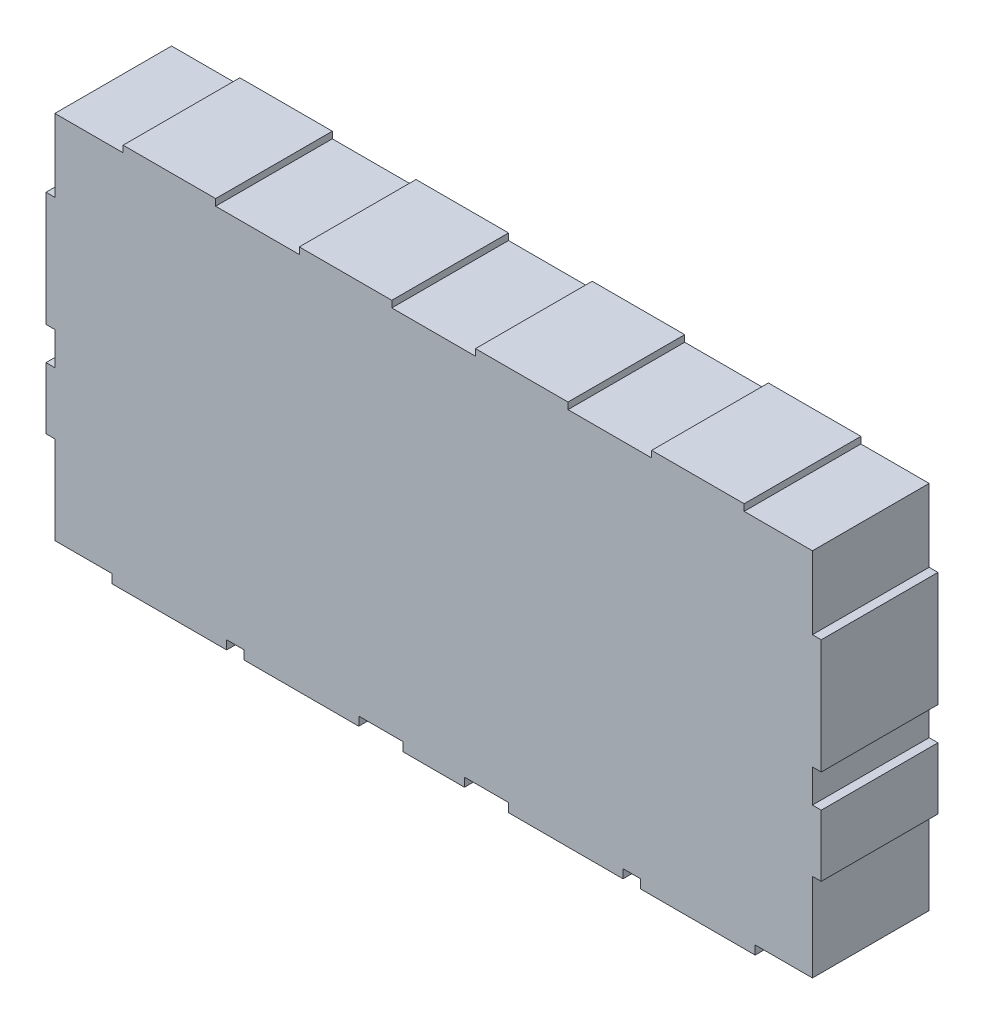
SolidWorks part; units mm, degrees
ref_plane "前视基准面" through (0, 0, 0) normal (0, 0, 1) x (1, 0, 0)
ref_plane "上视基准面" through (0, 0, 0) normal (0, 1, 0) x (1, 0, 0)
ref_plane "右视基准面" through (0, 0, 0) normal (1, 0, 0) x (0, 0, -1)
sketch "草图1" plane through (0, 0, 0) normal (0, 0, 1) x (1, 0, 0)
  line L0 (7.05, 4.35) -> (7.05, 4.2)
  line L1 (7.05, 4.2) -> (8.6, 4.2)
  line L2 (8.6, 4.2) -> (8.6, 2.55)
  line L3 (8.6, 2.55) -> (8.8, 2.55)
  line L4 (8.8, 2.55) -> (8.8, -0.05)
  line L5 (8.8, -0.05) -> (8.6, -0.05)
  line L6 (8.6, -0.05) -> (8.6, -0.8)
  line L7 (8.6, -0.8) -> (8.8, -0.8)
  line L8 (8.8, -0.8) -> (8.8, -2.2)
  line L9 (8.8, -2.2) -> (8.6, -2.2)
  line L10 (8.6, -2.2) -> (8.6, -4.2)
  line L11 (8.6, -4.2) -> (7.3, -4.2)
  line L12 (7.3, -4.2) -> (7.3, -4.4)
  line L13 (7.3, -4.4) -> (4.7, -4.4)
  line L14 (4.7, -4.4) -> (4.7, -4.2)
  line L15 (4.7, -4.2) -> (4.3, -4.2)
  line L16 (4.3, -4.2) -> (4.3, -4.4)
  line L17 (4.3, -4.4) -> (1.7, -4.4)
  line L18 (1.7, -4.4) -> (1.7, -4.2)
  line L19 (1.7, -4.2) -> (0.7, -4.2)
  line L20 (0.7, -4.2) -> (0.7, -4.4)
  line L21 (0.7, -4.4) -> (-0.7, -4.4)
  line L22 (-0.7, -4.4) -> (-0.7, -4.2)
  line L23 (-0.7, -4.2) -> (-1.7, -4.2)
  line L24 (-1.7, -4.2) -> (-1.7, -4.4)
  line L25 (-1.7, -4.4) -> (-4.3, -4.4)
  line L26 (-4.3, -4.4) -> (-4.3, -4.2)
  line L27 (-4.3, -4.2) -> (-4.7, -4.2)
  line L28 (-4.7, -4.2) -> (-4.7, -4.4)
  line L29 (-4.7, -4.4) -> (-7.3, -4.4)
  line L30 (-7.3, -4.4) -> (-7.3, -4.2)
  line L31 (-7.3, -4.2) -> (-8.6, -4.2)
  line L32 (-8.6, -4.2) -> (-8.6, -2.2)
  line L33 (-8.6, -2.2) -> (-8.8, -2.2)
  line L34 (-8.8, -2.2) -> (-8.8, -0.8)
  line L35 (-8.8, -0.8) -> (-8.6, -0.8)
  line L36 (-8.6, -0.8) -> (-8.6, -0.05)
  line L37 (-8.6, -0.05) -> (-8.8, -0.05)
  line L38 (-8.8, -0.05) -> (-8.8, 2.55)
  line L39 (-8.8, 2.55) -> (-8.6, 2.55)
  line L40 (-8.6, 2.55) -> (-8.6, 4.2)
  line L41 (-8.6, 4.2) -> (-7.05, 4.2)
  line L42 (-7.05, 4.2) -> (-7.05, 4.35)
  line L43 (-7.05, 4.35) -> (-4.95, 4.35)
  line L44 (-4.95, 4.35) -> (-4.95, 4.2)
  line L45 (-4.95, 4.2) -> (-3.05, 4.2)
  line L46 (-3.05, 4.2) -> (-3.05, 4.35)
  line L47 (-3.05, 4.35) -> (-0.95, 4.35)
  line L48 (-0.95, 4.35) -> (-0.95, 4.2)
  line L49 (-0.95, 4.2) -> (0.95, 4.2)
  line L50 (0.95, 4.2) -> (0.95, 4.35)
  line L51 (0.95, 4.35) -> (3.05, 4.35)
  line L52 (3.05, 4.35) -> (3.05, 4.2)
  line L53 (3.05, 4.2) -> (4.95, 4.2)
  line L54 (4.95, 4.2) -> (4.95, 4.35)
  line L55 (4.95, 4.35) -> (7.05, 4.35)
extrude "Component_Outline" add sketch "草图1" along normal blind 2.65 separate body
sketch3d "3D草图1"
  line L0 (0, 0, 0) -> (1, 0, 0)
  line L1 (0, 0, 0) -> (0, 1, 0)
  line L2 (0, 0, 0) -> (0, 0, 1)
  point P0 (0, 0, 0)
